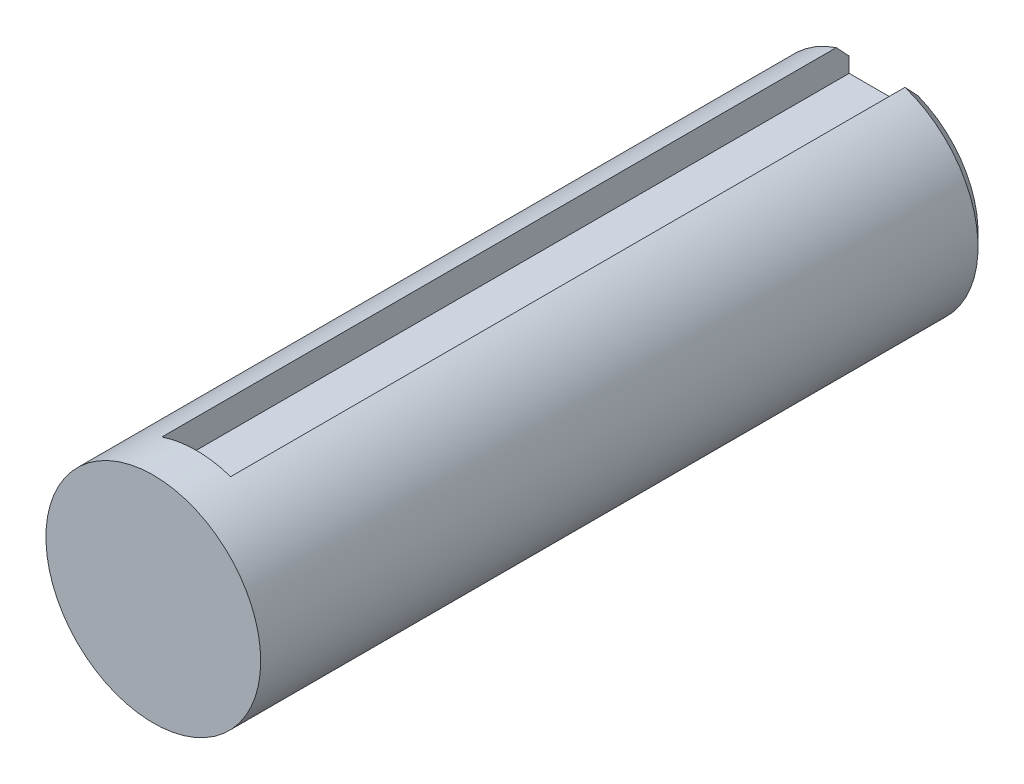
SolidWorks part; units mm, degrees
ref_plane "Front Plane" through (0, 0, 0) normal (0, 0, 1) x (1, 0, 0)
ref_plane "Top Plane" through (0, 0, 0) normal (0, 1, 0) x (1, 0, 0)
ref_plane "Right Plane" through (0, 0, 0) normal (1, 0, 0) x (0, 0, -1)
sketch "Sketch1" plane through (0, 0, 0) normal (0, 0, 1) x (1, 0, 0)
  line L0 (0, 0) -> (0, 12895.7132) construction
  line L1 (0, 0) -> (12895.7132, 0) construction
  circle A0 centre (0, 0) radius 12.5
  dimension "D1" = 25
extrude "Boss-Extrude1" add sketch "Sketch1" along normal blind 85
sketch "Sketch2" plane through (0, 0, 0) normal (0, 0, -1) x (-1, 0, 0)
  line L1 (-4, 16.5) -> (4, 16.5)
  line L2 (-4, 16.5) -> (-4, 8.5)
  line L3 (-4, 8.5) -> (4, 8.5)
  line L4 (4, 16.5) -> (4, 8.5)
  line L5 (-4, 16.5) -> (4, 8.5) construction
  line L6 (-4, 8.5) -> (4, 16.5) construction
  circle A0 centre (0, 0) radius 12.5 construction
  point P0 (0, 12.5)
  dimension "D1" = 8
  dimension "D2" = 4
extrude "Cut-Extrude1" cut sketch "Sketch2" against normal blind 80
chamfer "Chamfer1" distance 1.5 angle 45 1 edges at (0, -12.5, 0)
